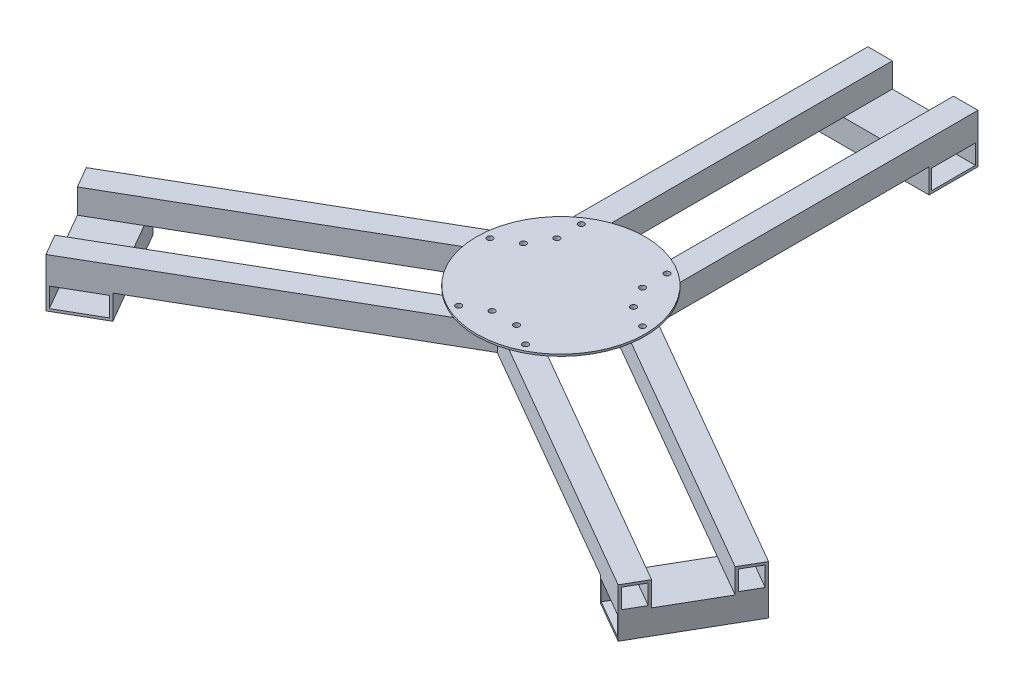
SolidWorks part; units mm, degrees
material "1060 Alloy"
ref_plane "Front Plane" through (0, 0, 0) normal (0, 0, 1) x (1, 0, 0)
ref_plane "Top Plane" through (0, 0, 0) normal (0, 1, 0) x (1, 0, 0)
ref_plane "Right Plane" through (0, 0, 0) normal (1, 0, 0) x (0, 0, -1)
sketch "Sketch1" plane through (0, 0, 0) normal (0, 1, 0) x (1, 0, 0)
  line L0 (-329.9557, -190.5) -> (0, 0) construction
  line L1 (0, 381) -> (0, 0) construction
  line L2 (0, 0) -> (329.9557, -190.5) construction
  line L3 (-305.4775, -227.6939) -> (22.225, -38.4948) construction
  line L4 (-349.9275, -150.7043) -> (-22.225, 38.4948) construction
  line L5 (-44.45, 378.3982) -> (-44.45, 0) construction
  line L6 (44.45, 378.3982) -> (44.45, 0) construction
  line L9 (-22.225, -38.4948) -> (305.4775, -227.6939) construction
  line L10 (22.225, 38.4948) -> (349.9275, -150.7043) construction
  line L12 (44.45, 381) -> (44.45, 0) construction
  line L13 (-44.45, 381) -> (-44.45, 0) construction
  line L14 (-352.1807, -152.0052) -> (-22.225, 38.4948) construction
  line L15 (-307.7307, -228.9948) -> (22.225, -38.4948) construction
  line L16 (22.225, 38.4948) -> (352.1807, -152.0052) construction
  line L17 (-22.225, -38.4948) -> (307.7307, -228.9948) construction
  circle A0 centre (0, 0) radius 381
  point P15 (323.6057, -201.4985)
  point P17 (336.3057, -179.5015)
  dimension "D1" = 762
  dimension "D2" = 120
  dimension "D3" = 44.45
  dimension "D6" = 44.45
  dimension "D9" = 120
  dimension "D4" = 44.45
  dimension "D5" = 44.45
  dimension "D7" = 44.45
  dimension "D8" = 44.45
ref_plane "Plane2" through (0, 0, -12.7) normal (0, 0, 1) x (1, 0, 0)
sketch "Sketch6" plane through (0, 0, -12.7) normal (0, 0, 1) x (1, 0, 0)
  line L0 (-54.61, 10.16) -> (-34.29, 10.16)
  line L1 (-57.15, -12.7) -> (-31.75, -12.7)
  line L2 (-57.15, -12.7) -> (-57.15, 12.7)
  line L3 (-57.15, 12.7) -> (-31.75, 12.7)
  line L4 (-31.75, -12.7) -> (-31.75, 12.7)
  line L5 (-57.15, -12.7) -> (-31.75, 12.7) construction
  line L6 (-57.15, 12.7) -> (-31.75, -12.7) construction
  line L7 (-34.29, -10.16) -> (-34.29, 10.16)
  line L8 (-54.61, -10.16) -> (-34.29, -10.16)
  line L9 (-54.61, -10.16) -> (-54.61, 10.16)
  line L10 (0, 0) -> (0, 75.873) construction
  line L11 (57.15, 12.7) -> (31.75, -12.7) construction
  line L12 (57.15, -12.7) -> (31.75, 12.7) construction
  line L13 (54.61, -10.16) -> (54.61, 10.16)
  line L14 (54.61, -10.16) -> (34.29, -10.16)
  line L15 (34.29, -10.16) -> (34.29, 10.16)
  line L16 (31.75, -12.7) -> (31.75, 12.7)
  line L17 (57.15, 12.7) -> (31.75, 12.7)
  line L18 (57.15, -12.7) -> (57.15, 12.7)
  line L19 (57.15, -12.7) -> (31.75, -12.7)
  line L20 (54.61, 10.16) -> (34.29, 10.16)
  point P0 (-44.45, 0)
  point P19 (44.45, 0)
  dimension "D1" = 25.4
  dimension "D2" = 25.4
  dimension "D3" = 0
  dimension "D4" = 0
  dimension "D5" = 2.54
extrude "Boss-Extrude3" add sketch "Sketch6" against normal blind 363.22
ref_plane "Plane3" through (-57.15, 0, 0) normal (1, 0, 0) x (0, 0, -1)
sketch "Sketch7" plane through (-57.15, 0, 0) normal (1, 0, 0) x (0, 0, -1)
  line L0 (373.38, -35.5199) -> (327.66, -35.5199)
  line L1 (375.92, -12.7) -> (325.12, -12.7)
  line L2 (375.92, -12.7) -> (375.92, -38.0599)
  line L3 (375.92, -38.0599) -> (325.12, -38.0599)
  line L4 (325.12, -12.7) -> (325.12, -38.0599)
  line L5 (327.66, -15.24) -> (327.66, -35.5199)
  line L6 (373.38, -15.24) -> (327.66, -15.24)
  line L7 (373.38, -15.24) -> (373.38, -35.5199)
  dimension "D1" = 50.8
  dimension "D2" = 25.3599
  dimension "D3" = 2.54
extrude "Boss-Extrude4" add sketch "Sketch7" along normal blind 114.3
sketch "Sketch8" plane through (0, 0, 0) normal (0, 1, 0) x (1, 0, 0)
  line L0 (0, 0) -> (0, 589.3312) construction
sketch "Sketch9" plane through (0, 12.7, 0) normal (0, 1, 0) x (1, 0, 0)
  line L0 (0, 0) -> (-71.5007, 41.2809)
  line L1 (-71.5007, 41.2809) -> (-64.8463, -9.6574)
  line L2 (-64.8463, -9.6574) -> (0, 0)
  line L3 (0, 0) -> (66.1664, 38.2012)
  line L4 (66.1664, 38.2012) -> (56.5317, -13.1953)
  line L5 (56.5317, -13.1953) -> (0, 0)
  line L6 (0, 0) -> (329.9557, -190.5) construction
  line L7 (-329.9557, -190.5) -> (0, 0) construction
  dimension "D1" = 180
  dimension "D2" = 180
extrude "Cut-Extrude1" cut sketch "Sketch9" against normal through all contours L3 L4 L5
sketch "Sketch10" plane through (0, 12.7, 0) normal (0, 1, 0) x (1, 0, 0)
  line L0 (0, 0) -> (-91.3571, 52.7451)
  line L1 (-91.3571, 52.7451) -> (-72.0511, -19.306)
  line L2 (-72.0511, -19.306) -> (0, 0)
  line L3 (0, 0) -> (329.9557, -190.5) construction
  dimension "D1" = 180
extrude "Cut-Extrude2" cut sketch "Sketch10" against normal through all
pattern_circular "CirPattern1" count 3 over 360 about axis through (0, 0, 0) along (0, 1, 0) of bodies 114
sketch "Sketch12" plane through (0, 12.7, 0) normal (0, 1, 0) x (1, 0, 0)
  line L0 (57.15, 375.92) -> (57.15, 32.9956) construction
  line L2 (31.75, 18.3309) -> (57.15, 32.9956) construction
  circle A0 centre (44.45, 40.3279) radius 3
  circle A1 centre (57.15, 18.3309) radius 3
  dimension "D1" = 12.7
  dimension "D3" = 6
  dimension "D2" = 12.7
extrude "Cut-Extrude3" cut sketch "Sketch12" against normal through all
sketch "Sketch13" plane through (0, 12.7, 0) normal (0, 1, 0) x (1, 0, 0)
  circle A0 centre (0, 0) radius 87.5
  dimension "D1" = 175
extrude "Boss-Extrude6" add sketch "Sketch13" along normal blind 2
sketch "Sketch14" plane through (0, -12.7, 0) normal (0, -1, 0) x (1, 0, 0)
  line L0 (0, 0) -> (57.15, -32.9956) construction
  line L1 (57.15, -18.3309) -> (82.398, -3.7539) construction
  line L2 (57.15, -375.92) -> (57.15, -66.258) construction
  line L3 (0, 0) -> (0, 65.9911) construction
  line L4 (0, 0) -> (-57.15, -32.9956) construction
  circle A0 centre (57.15, -18.3309) radius 3
  circle A1 centre (44.45, -40.3279) radius 3
  circle A2 centre (-57.15, -18.3309) radius 3
  circle A3 centre (-44.45, -40.3279) radius 3
  circle A4 centre (12.7, 58.6588) radius 3
  circle A5 centre (-12.7, 58.6588) radius 3
  circle A6 centre (44.45, -65.7279) radius 3
  circle A7 centre (79.147, -5.6309) radius 3
  circle A8 centre (34.697, 71.3588) radius 3
  circle A9 centre (-34.697, 71.3588) radius 3
  circle A10 centre (-79.147, -5.6309) radius 3
  circle A11 centre (-44.45, -65.7279) radius 3
  point P20 (0, 0)
  point P39 (0, 0)
  dimension "D1" = 6
  dimension "D2" = 6
  dimension "D4" = 6
  dimension "D6" = 120
  dimension "D7" = 6
  dimension "D3" = 3
  dimension "D5" = 25.4
  dimension "D8" = 25.4
  dimension "D9" = 3
extrude "Cut-Extrude4" cut sketch "Sketch14" against normal through all
